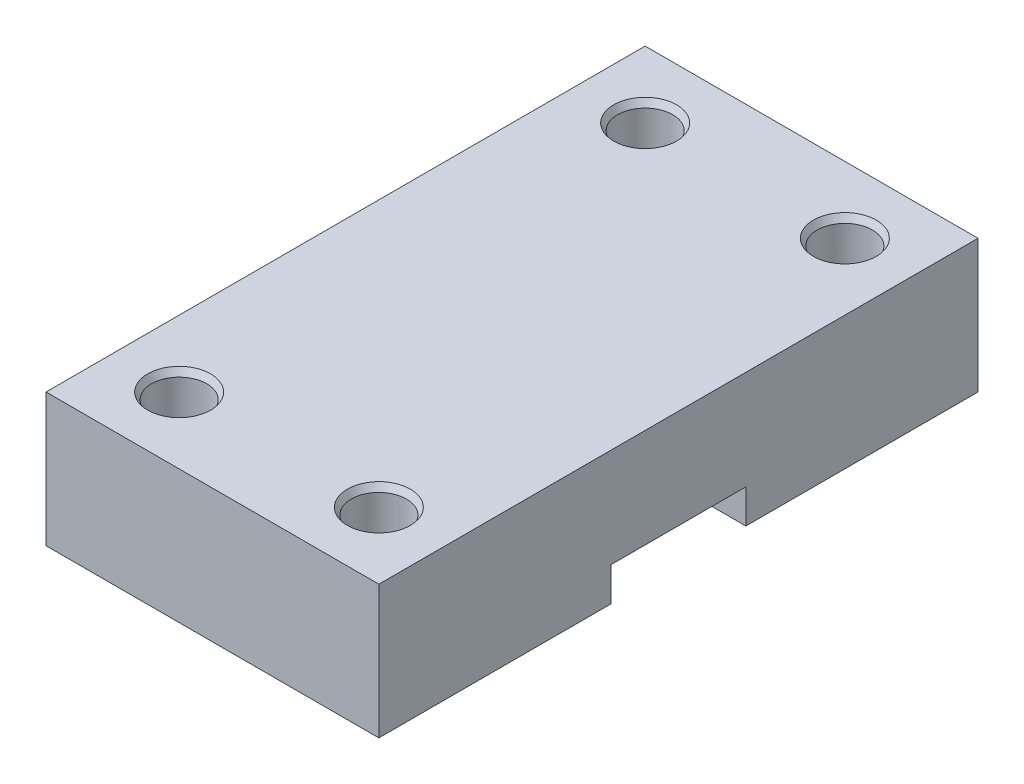
SolidWorks part; units mm, degrees
ref_plane "Спереди" through (0, 0, 0) normal (0, 0, 1) x (1, 0, 0)
ref_plane "Сверху" through (0, 0, 0) normal (0, 1, 0) x (1, 0, 0)
ref_plane "Справа" through (0, 0, 0) normal (1, 0, 0) x (0, 0, -1)
sketch "Sketch1" plane through (0, 0, 0) normal (0, 1, 0) x (1, 0, 0)
  line L1 (25, -45) -> (-25, -45)
  line L2 (25, -45) -> (25, 45)
  line L3 (25, 45) -> (-25, 45)
  line L4 (-25, -45) -> (-25, 45)
  line L5 (25, -45) -> (-25, 45) construction
  line L6 (25, 45) -> (-25, -45) construction
  point P0 (0, 0)
  dimension "D1" = 50
  dimension "D2" = 90
extrude "Boss-Extrude1" add sketch "Sketch1" along normal blind 20
sketch "Sketch2" plane through (25, 0, 0) normal (1, 0, 0) x (0, 0, -1)
  line L0 (0, 0) -> (0, 20) construction
  line L1 (-45, 0) -> (45, 0) construction
  line L2 (-45, 20) -> (45, 20) construction
  line L4 (10.125, 5.1) -> (-10.125, 5.1)
  line L5 (10.125, 5.1) -> (10.125, 0)
  line L6 (10.125, 0) -> (-10.125, 0)
  line L7 (-10.125, 5.1) -> (-10.125, 0)
  line L8 (10.125, 5.1) -> (-10.125, 0) construction
  line L9 (10.125, 0) -> (-10.125, 5.1) construction
  point P6 (0, 2.55)
  dimension "D1" = 20.25
  dimension "D2" = 5.1
extrude "Cut-Extrude1" cut sketch "Sketch2" against normal through all and the other way through all
sketch "Sketch3" plane through (0, 0, 0) normal (0, -1, 0) x (1, 0, 0)
  line L0 (-15, 35) -> (15, -35) construction
  line L1 (-15, -35) -> (15, 35) construction
  line L2 (0, 45) -> (0, -45) construction
  line L3 (25, 35) -> (-25, 35) construction
  line L4 (25, 45) -> (25, 10.125) construction
  line L5 (-25, 10.125) -> (-25, 45) construction
  line L6 (-25, -35) -> (25, -35) construction
  line L7 (-25, -45) -> (-25, -10.125) construction
  line L8 (25, -10.125) -> (25, -45) construction
  line L9 (-25, 45) -> (25, 45) construction
  line L10 (25, -45) -> (-25, -45) construction
  circle A0 centre (-15, 35) radius 4.15
  circle A1 centre (-15, -35) radius 4.15
  circle A2 centre (15, 35) radius 4.15
  circle A3 centre (15, -35) radius 4.15
  point P6 (0, 0)
  point P7 (0, 0)
  dimension "D1" = 8.3
  dimension "D2" = 30
  dimension "D3" = 70
extrude "Cut-Extrude2" cut sketch "Sketch3" against normal through all
chamfer "Chamfer1" distance 1 angle 30 4 edges at (-15, 20, -39.15) (15, 20, -39.15) (15, 20, 30.85) (-15, 20, 30.85)
